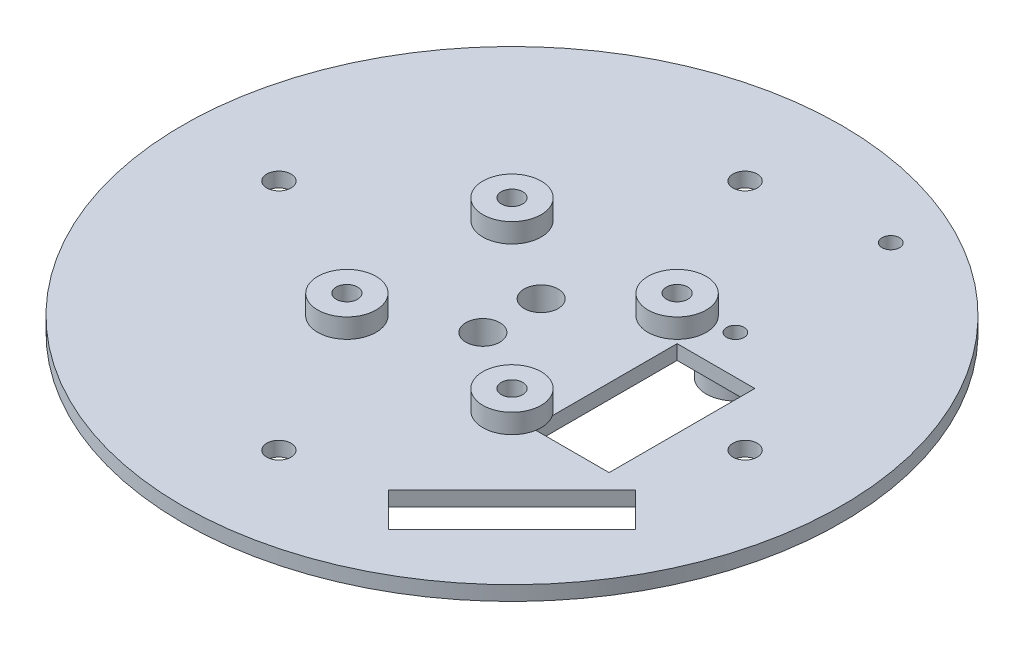
SolidWorks part; units mm, degrees
ref_plane "前视基准面" through (0, 0, 0) normal (0, 0, 1) x (1, 0, 0)
ref_plane "上视基准面" through (0, 0, 0) normal (0, 1, 0) x (1, 0, 0)
ref_plane "右视基准面" through (0, 0, 0) normal (1, 0, 0) x (0, 0, -1)
sketch "草图1" plane through (0, 0, 0) normal (0, 1, 0) x (1, 0, 0)
  line L0 (0, -28.3374) -> (0, 58.5252) construction
  line L1 (-49.5021, 0) -> (67.6509, 0) construction
  line L14 (0, 18) -> (35.2299, 18) construction
  line L15 (21.9203, -9.1924) -> (9.1924, -21.9203)
  line L16 (11, 6) -> (19, 6)
  line L17 (11, 6) -> (11, -9)
  line L18 (11, -9) -> (19, -9)
  line L19 (19, 6) -> (19, -9)
  line L20 (9.1924, -21.9203) -> (12.7279, -25.4558)
  line L21 (12.7279, -25.4558) -> (25.4558, -12.7279)
  line L22 (25.4558, -12.7279) -> (21.9203, -9.1924)
  line L23 (0, 0) -> (15.5563, -15.5563) construction
  circle A8 centre (0, 0) radius 24 construction
  circle A9 centre (0, 24) radius 1.25
  circle A10 centre (24, 0) radius 1.25
  circle A11 centre (0, -24) radius 1.25
  circle A12 centre (-24, 0) radius 1.25
  circle A13 centre (8.5, 8.5) radius 1.1
  circle A14 centre (-8.5, 8.5) radius 1.1
  circle A15 centre (8.5, -8.5) radius 1.1
  circle A16 centre (-8.5, -8.5) radius 1.1
  circle A17 centre (0, 0) radius 33.93
  circle A18 centre (0, 3) radius 1.75
  circle A19 centre (0, -3) radius 1.75
  circle A20 centre (13, 10) radius 0.9
  circle A21 centre (13, 26) radius 0.9
  point P13 (0, 45)
  point P14 (45, 0)
  point P15 (-45, 0)
  dimension "D4" = 3.5
  dimension "D7" = 48
  dimension "D8" = 2.5
  dimension "D9" = 2.5
  dimension "D10" = 2.5
  dimension "D11" = 2.5
  dimension "D12" = 2.2
  dimension "D13" = 17
  dimension "D14" = 17
  dimension "D2" = 6
  dimension "D3" = 3.5
  dimension "D5" = 3
  dimension "D6" = 16
  dimension "D15" = 1.8
  dimension "D16" = 18
  dimension "D17" = 13
  dimension "D18" = 15
  dimension "D19" = 8
  dimension "D20" = 11
  dimension "D21" = 6
  dimension "D22" = 22
  dimension "D23" = 45
  dimension "D24" = 18
  dimension "D25" = 5
extrude "凸台-拉伸1" add sketch "草图1" along normal blind 1.5
sketch "草图2" plane through (0, 1.5, 0) normal (0, 1, 0) x (1, 0, 0)
  circle A0 centre (-8.5, 8.5) radius 3
  circle A1 centre (8.5, 8.5) radius 3
  circle A2 centre (8.5, -8.5) radius 3
  circle A3 centre (-8.5, -8.5) radius 3
  circle A4 centre (-8.5, 8.5) radius 1.1 construction
  circle A5 centre (-8.5, 8.5) radius 1.1
  circle A6 centre (8.5, 8.5) radius 1.1 construction
  circle A7 centre (8.5, 8.5) radius 1.1
  circle A8 centre (-8.5, -8.5) radius 1.1 construction
  circle A9 centre (-8.5, -8.5) radius 1.1
  circle A10 centre (8.5, -8.5) radius 1.1 construction
  circle A11 centre (8.5, -8.5) radius 1.1
  dimension "D1" = 6
  dimension "D2" = 6
  dimension "D3" = 6
  dimension "D4" = 6
extrude "凸台-拉伸2" add sketch "草图2" along normal blind 2
sketch "草图3" plane through (0, 0, 0) normal (0, -1, 0) x (1, 0, 0)
  line L0 (0, 8) -> (0, -41.034) construction
  line L1 (5, 8) -> (-5, 8)
  line L2 (-5, 8) -> (-5, -7)
  line L3 (-5, -7) -> (5, -7)
  line L4 (5, 8) -> (5, -7)
  circle A0 centre (0, 3) radius 1.75 construction
  circle A1 centre (0, 3) radius 1.75
  circle A2 centre (0, -3) radius 1.75 construction
  circle A3 centre (0, -3) radius 1.75
  point P13 (0, -7)
  dimension "D1" = 15
  dimension "D2" = 10
  dimension "D3" = 5
extrude "凸台-拉伸3" add sketch "草图3" along normal blind 1
sketch "草图5" plane through (0, 0, 0) normal (0, -1, 0) x (1, 0, 0)
  circle A0 centre (13, -10) radius 0.9 construction
  circle A1 centre (13, -26) radius 0.9 construction
  circle A2 centre (13, -10) radius 0.9
  circle A3 centre (13, -26) radius 0.9
  circle A4 centre (13, -26) radius 3
  circle A5 centre (13, -10) radius 3
  dimension "D1" = 6
  dimension "D2" = 6
extrude "凸台-拉伸5" add sketch "草图5" along normal blind 2.5
